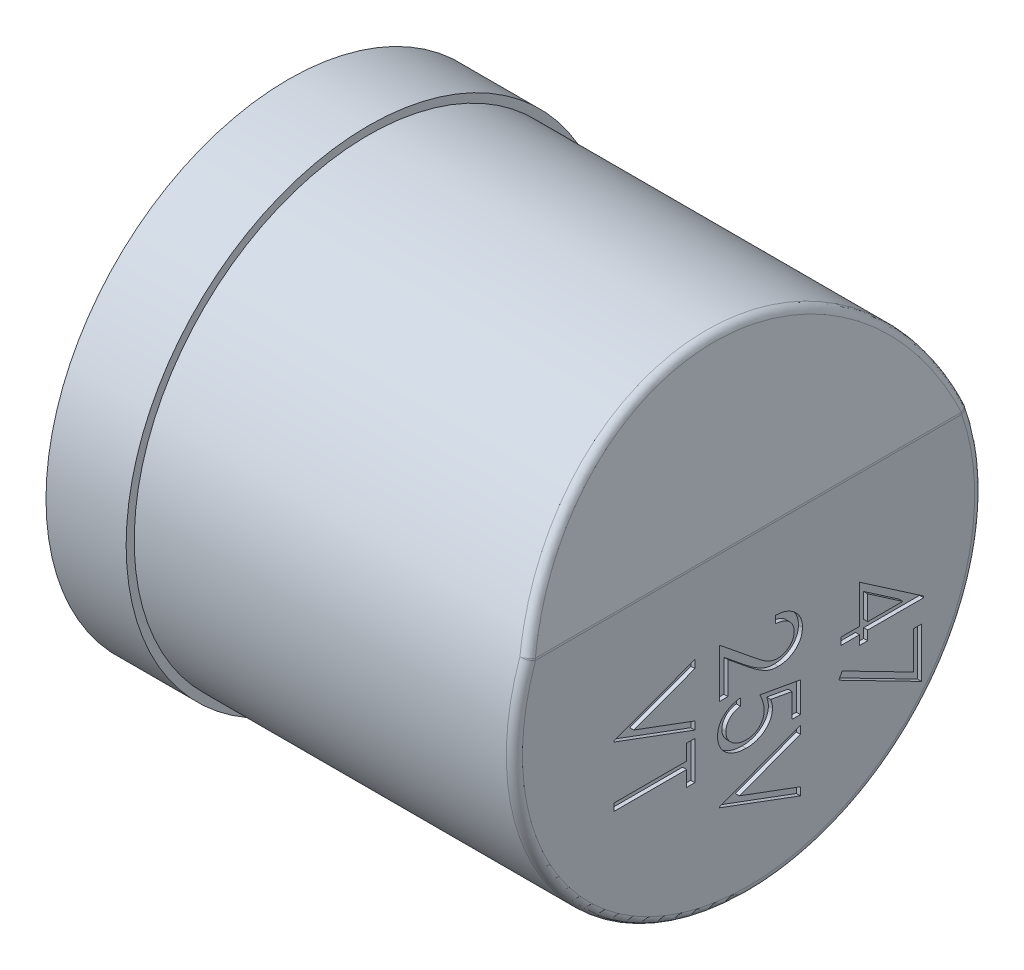
SolidWorks part; units mm, degrees
ref_plane "Plan de face" through (0, 0, 0) normal (0, 0, 1) x (1, 0, 0)
ref_plane "Plan de dessus" through (0, 0, 0) normal (0, 1, 0) x (1, 0, 0)
ref_plane "Plan de droite" through (0, 0, 0) normal (1, 0, 0) x (0, 0, -1)
sketch "Esquisse1" plane through (0, 0, 0) normal (0, 0, 1) x (1, 0, 0)
  line L0 (0, 0) -> (0, 3)
  line L1 (0, 3) -> (0.9923, 3)
  line L2 (0.9923, 3) -> (0.9923, 2.9)
  line L3 (0.9923, 2.9) -> (5.7, 2.9)
  line L4 (5.7, 2.9) -> (5.7, 0)
  line L5 (5.7, 0) -> (0, 0)
  dimension "D1" = 5.7
  dimension "D2" = 3
  dimension "D3" = 2.9
revolve "Révolution1" add sketch "Esquisse1" angle 360 about L5
sketch "Esquisse2" plane through (0, 0, 0) normal (0, 0, 1) x (1, 0, 0)
  line L0 (5.2569, 2.9) -> (5.7, 0.9497)
  line L1 (5.7, 2.9) -> (0.9923, 2.9) construction
  line L2 (5.7, -2.9) -> (5.7, 2.9) construction
  line L3 (5.2569, 2.9) -> (6.0953, 3.0904)
  line L4 (6.0953, 3.0904) -> (6.5383, 1.1401)
  line L5 (6.5383, 1.1401) -> (5.7, 0.9497)
  dimension "D1" = 2
extrude "Enlèv. mat.-Extru.1" cut sketch "Esquisse2" against normal mid plane 10
fillet "Congé1" radius 0.1 3 edges at (5.2569, 2.9, 0) (5.7, 0.9497, 0) (5.7, -2.9, 0)
sketch "Esquisse3" plane through (5.7, 0, 0) normal (1, 0, 0) x (0, 0, -1)
  line L0 (-0.3583, 0) -> (-0.3583, -1.918) construction
  line L1 (-1.665, 0) -> (-1.665, -1.918) construction
  line L2 (1.1423, 0) -> (1.1423, -1.918) construction
  text T0 "47" font "Century Gothic" height 1
  text T1 "25V" font "Century Gothic" height 1
  text T2 "VT" font "Century Gothic" height 1
extrude "Enlèv. mat.-Extru.2" cut sketch "Esquisse3" against normal blind 0.05
